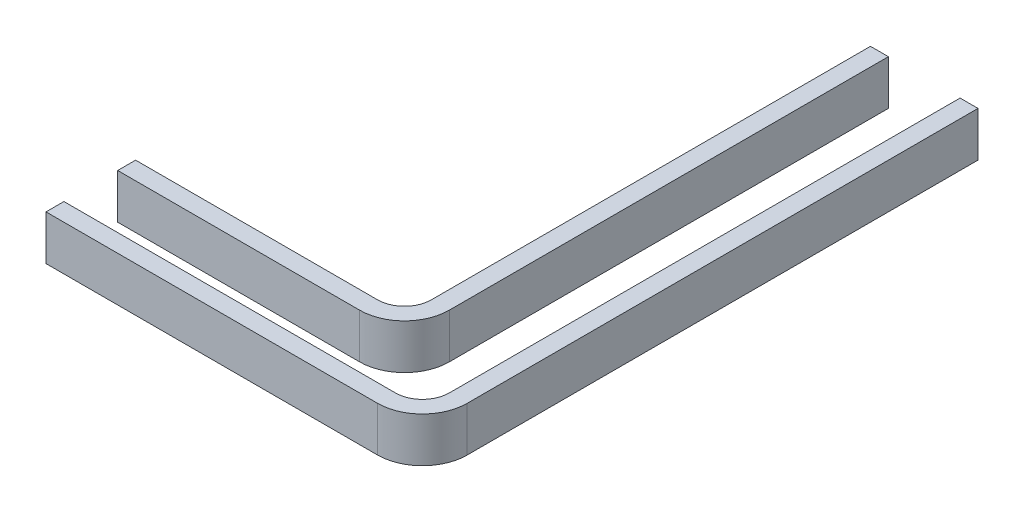
SolidWorks part; units mm, degrees
ref_plane "前视基准面" through (0, 0, 0) normal (0, 0, 1) x (1, 0, 0)
ref_plane "上视基准面" through (0, 0, 0) normal (0, 1, 0) x (1, 0, 0)
ref_plane "右视基准面" through (0, 0, 0) normal (1, 0, 0) x (0, 0, -1)
sketch "草图1" plane through (0, 0, 0) normal (0, 1, 0) x (1, 0, 0)
  line L0 (40, -5) -> (42, -5)
  line L1 (0, 3) -> (40, 3)
  line L2 (0, 3) -> (0, -3)
  line L3 (0, -3) -> (40, -3)
  line L4 (40, 3) -> (40, -3)
  line L5 (0, 3) -> (40, -3) construction
  line L6 (0, -3) -> (40, 3) construction
  line L7 (32, 57) -> (40, 57)
  line L8 (32, 57) -> (32, -3)
  line L9 (32, -3) -> (40, -3)
  line L10 (40, 57) -> (40, -3)
  line L11 (32, 57) -> (40, -3) construction
  line L12 (32, -3) -> (40, 57) construction
  line L13 (0, -5) -> (40, -5)
  line L14 (0, -5) -> (0, 5)
  line L15 (0, 5) -> (40, 5)
  line L16 (40, -5) -> (40, 5)
  line L17 (0, -5) -> (40, 5) construction
  line L18 (0, 5) -> (40, -5) construction
  line L19 (42, 57) -> (30, 57)
  line L20 (42, 57) -> (42, -3)
  line L21 (42, -3) -> (30, -3)
  line L22 (30, 57) -> (30, -3)
  line L23 (42, 57) -> (30, -3) construction
  line L24 (42, -3) -> (30, 57) construction
  line L25 (42, -5) -> (42, -3)
  line L27 (42, 57) -> (30, 57)
  line L28 (42, 57) -> (42, 60)
  line L29 (42, 60) -> (30, 60)
  line L30 (30, 57) -> (30, 60)
  point P0 (20, 0)
  point P6 (36, 27)
  point P7 (20, 0)
  point P15 (36, 27)
  point P23 (0, 0)
  point P24 (-12.02, 6.1796)
  point P25 (47.2884, -2.7882)
  point P26 (0, 0)
  dimension "D1" = 6
  dimension "D2" = 40
  dimension "D3" = 8
  dimension "D4" = 60
  dimension "D5" = 12
  dimension "D6" = 10
  dimension "D7" = 3
extrude "凸台-拉伸1" add sketch "草图1" along normal blind 5 contours L22 L15 L14 L1 | L13 L16 L3 L14 | L0 L25 L21 L16 | L21 L20 L19 L10 L4 | L19 L22 L15 L8 | L15 L22 L1 L8 | L28 L27 L30 L29
fillet "圆角1" radius 5 2 edges at (32, 2.5, -3) (42, 2.5, 5)
fillet "圆角2" radius 3 2 edges at (40, 2.5, 3) (30, 2.5, -5)
sketch "草图2" plane through (0, 5, 0) normal (0, 1, 0) x (1, 0, 0)
  line L0 (30, 60) -> (30, 8) construction
  line L1 (30, 57) -> (42, 57)
  line L2 (30, 57) -> (30, 60)
  line L3 (30, 60) -> (42, 60)
  line L4 (42, 57) -> (42, 60)
  line L5 (40, 57) -> (32, 57) construction
extrude "切除-拉伸1" cut sketch "草图2" against normal through all both and the other way through all
